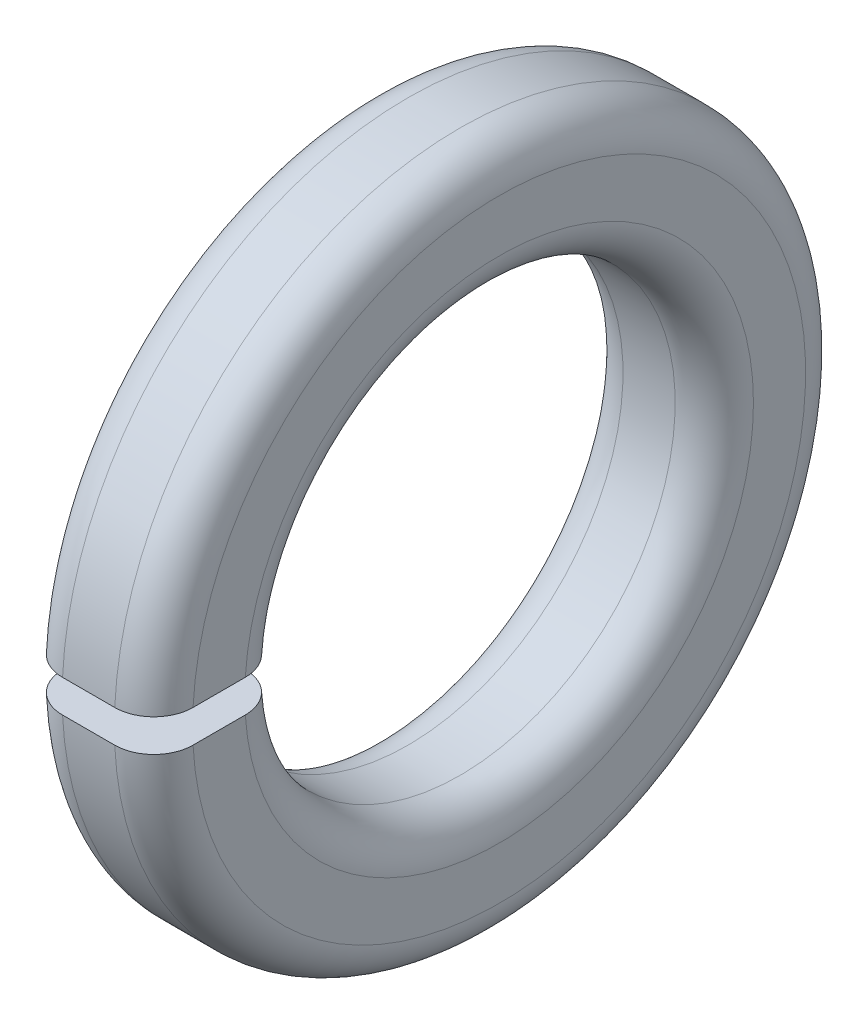
SolidWorks part; units mm, degrees
ref_plane "Plane1" through (0, 0, 0) normal (0, 0, 1) x (1, 0, 0)
ref_plane "Plane2" through (0, 0, 0) normal (0, 1, 0) x (1, 0, 0)
ref_plane "Plane3" through (0, 0, 0) normal (1, 0, 0) x (0, 0, -1)
sketch "Sketch1" plane through (0, 0, 0) normal (0, 0, 1) x (1, 0, 0)
  line L0 (-34.925, 0) -> (9.525, 0) construction
  line L1 (0, 1.95) -> (0, 2.35)
  line L2 (-0.3, 2.65) -> (-0.7, 2.65)
  line L3 (-1, 2.35) -> (-1, 1.95)
  line L4 (-0.7, 1.65) -> (-0.3, 1.65)
  arc A0 (-0.7, 1.65) -> (-1, 1.95) centre (-0.7, 1.95) cw
  arc A1 (0, 1.95) -> (-0.3, 1.65) centre (-0.3, 1.95) cw
  arc A2 (0, 2.35) -> (-0.3, 2.65) centre (-0.3, 2.35) ccw
  arc A3 (-0.7, 2.65) -> (-1, 2.35) centre (-0.7, 2.35) ccw
  point P8 (-1, 1.65)
  point P14 (0, 2.65)
  point P17 (-1, 2.65)
  dimension "Fillet_rad" = 0.3
  dimension "Thickness" = 1
  dimension "Inside_dia" = 3.3
  dimension "Outside_dia" = 5.3
revolve "Base-Revolve" add sketch "Sketch1" angle 360 about L0
sketch "Sketch2" plane through (0, 0, 0) normal (-1, 0, 0) x (0, -1, 0)
  line L0 (-0.125, 0) -> (0.125, 0)
  line L1 (0, 0) -> (0, 12.7) construction
  line L2 (0.125, 0) -> (0.125, 2.703)
  line L3 (0.125, 2.703) -> (-0.125, 2.703)
  line L4 (-0.125, 2.703) -> (-0.125, 0)
  dimension "D1" = 0.25
  dimension "D2" = 2.703
extrude "Gap" cut sketch "Sketch2" along normal through all
equation "\"D1@Sketch2\" = \"Thickness@Sketch1\" * 0.25"
equation "\"Outside_dia@Sketch1\" = \"Inside_dia@Sketch1\" + 2.0 * \"Thickness@Sketch1\""
equation "\"D2@Sketch2\" = \"Outside_dia@Sketch1\" * 0.51"
